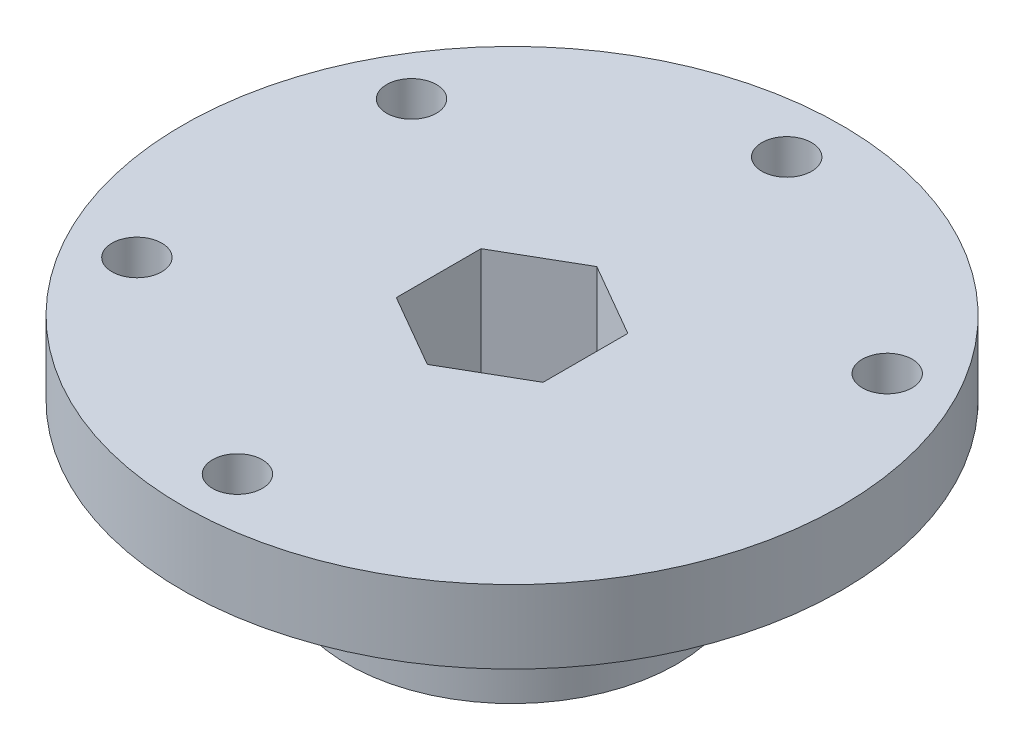
SolidWorks part; units mm, degrees
ref_plane "Front Plane" through (0, 0, 0) normal (0, 0, 1) x (1, 0, 0)
ref_plane "Top Plane" through (0, 0, 0) normal (0, 1, 0) x (1, 0, 0)
ref_plane "Right Plane" through (0, 0, 0) normal (1, 0, 0) x (0, 0, -1)
sketch "Sketch1" plane through (0, 0, 0) normal (0, 0, 1) x (1, 0, 0)
  line L0 (28.575, 0) -> (0, 0)
  line L1 (0, 0) -> (0, -6.35)
  line L2 (0, -6.35) -> (28.575, -6.35)
  line L3 (28.575, -6.35) -> (28.575, 0)
  line L4 (0, 0) -> (0, -6.35) construction
revolve "Revolve1" add sketch "Sketch1" angle 360 about L4
sketch "Sketch2" plane through (0, -6.35, 0) normal (0, -1, 0) x (1, 0, 0)
  circle A0 centre (0, 0) radius 14.2748
extrude "Boss-Extrude1" add sketch "Sketch2" along normal blind 12.7
sketch "Sketch3" plane through (0, 0, 0) normal (0, 1, 0) x (-1, 0, 0)
  line L0 (0, -7.347) -> (6.3627, -3.6735)
  line L1 (6.3627, -3.6735) -> (6.3627, 3.6735)
  line L2 (6.3627, 3.6735) -> (0, 7.347)
  line L3 (0, 7.347) -> (-6.3627, 3.6735)
  line L4 (-6.3627, 3.6735) -> (-6.3627, -3.6735)
  line L5 (-6.3627, -3.6735) -> (0, -7.347)
extrude "Cut-Extrude1" cut sketch "Sketch3" against normal through all
hole_wizard "#8 Clearance Hole1" positions "Sketch5" profile "Sketch4" hole size "#8" standard "ANSI Inch"
sketch "Sketch5" plane through (0, -6.35, 0) normal (0, -1, 0) x (1, 0, 0)
  point P0 (-20.6222, -11.9062)
  point P1 (0, 23.8125)
  point P2 (-20.6222, -11.9062)
  point P3 (0, -23.8125)
  point P4 (-20.6222, 11.9062)
  point P5 (20.6222, -11.9062)
sketch "Sketch4" plane through (-20.6222, -6.35, -11.9062) normal (1, 0, 0) x (0, 0, -1)
  line L0 (0, 0) -> (0, 6.35)
  line L1 (0, 6.35) -> (2.159, 6.35)
  line L2 (2.159, 6.35) -> (2.159, 0)
  line L5 (2.159, 0) -> (0, 0)
  line L11 (0, -6.35) -> (0, 107.95) construction
  dimension "Thru Hole Dia." = 4.318
  dimension "Thru Hole Depth" = 6.35
